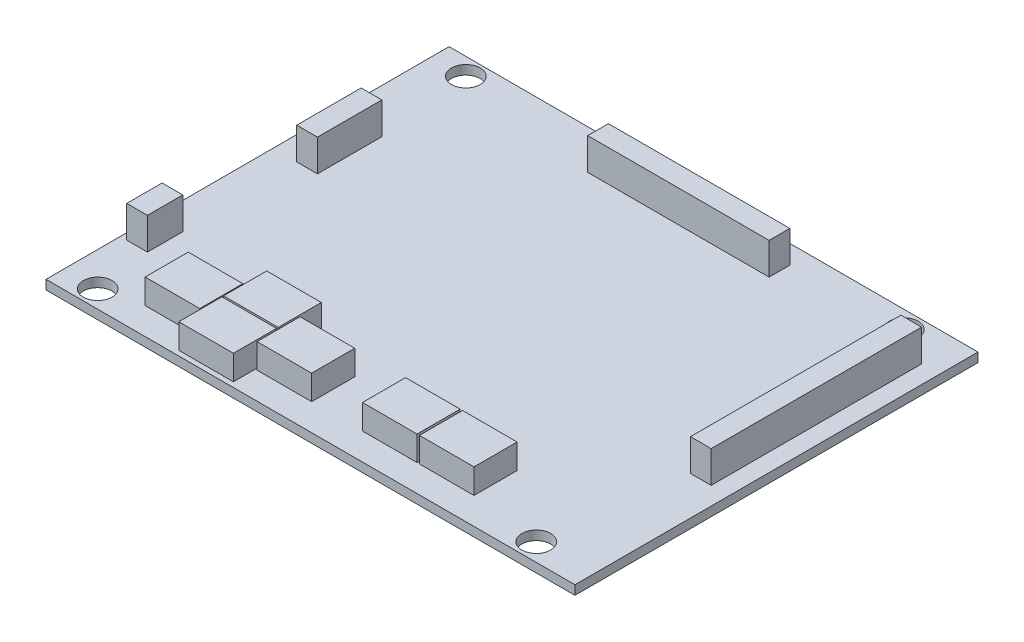
SolidWorks part; units mm, degrees
ref_plane "Front Plane" through (0, 0, 0) normal (0, 0, 1) x (1, 0, 0)
ref_plane "Top Plane" through (0, 0, 0) normal (0, 1, 0) x (1, 0, 0)
ref_plane "Right Plane" through (0, 0, 0) normal (1, 0, 0) x (0, 0, -1)
sketch "Sketch1" plane through (0, 0, 0) normal (0, 1, 0) x (1, 0, 0)
  line L1 (0, 0) -> (92, 0)
  line L2 (0, 0) -> (0, 70.1)
  line L3 (0, 70.1) -> (92, 70.1)
  line L4 (92, 0) -> (92, 70.1)
  circle A0 centre (5.92, 3.07) radius 2.5
  circle A1 centre (82.16, 3.11) radius 2.5
  circle A2 centre (82.16, 67.05) radius 2.5
  circle A3 centre (5.92, 67.1) radius 2.5
  dimension "D3" = 5.92
  dimension "D1" = 92
  dimension "D2" = 70.1
  dimension "D4" = 3.07
  dimension "D5" = 9.84
  dimension "D6" = 3.11
  dimension "D7" = 9.84
  dimension "D8" = 3.05
  dimension "D9" = 3
  dimension "D10" = 5.92
extrude "Y+ PCB extr" add sketch "Sketch1" along normal blind 1.6
sketch "Sketch2" plane through (0, 1.6, 0) normal (0, 1, 0) x (1, 0, 0)
  line L0 (0, 70.1) -> (0, 0) construction
  line L1 (31, 66.82) -> (62.55, 66.82)
  line L2 (31, 66.82) -> (31, 63.22)
  line L3 (31, 63.22) -> (62.55, 63.22)
  line L4 (62.55, 66.82) -> (62.55, 63.22)
  line L5 (4.12, 50.69) -> (7.72, 50.69)
  line L6 (4.12, 50.69) -> (4.12, 39.49)
  line L7 (4.12, 39.49) -> (7.72, 39.49)
  line L8 (7.72, 50.69) -> (7.72, 39.49)
  line L9 (1.12, 19.07) -> (4.72, 19.07)
  line L10 (1.12, 19.07) -> (1.12, 12.92)
  line L11 (1.12, 12.92) -> (4.72, 12.92)
  line L12 (4.72, 19.07) -> (4.72, 12.92)
  line L13 (85.28, 63.41) -> (88.88, 63.41)
  line L14 (85.28, 63.41) -> (85.28, 26.81)
  line L15 (85.28, 26.81) -> (88.88, 26.81)
  line L16 (88.88, 63.41) -> (88.88, 26.81)
  line L17 (92, 70.1) -> (0, 70.1) construction
  line L18 (92, 0) -> (92, 70.1) construction
  line L19 (0, 0) -> (92, 0) construction
  dimension "D1" = 31
  dimension "D2" = 3.28
  dimension "D3" = 3.6
  dimension "D4" = 31.55
  dimension "D5" = 6.69
  dimension "D6" = 3.12
  dimension "D7" = 3.6
  dimension "D8" = 36.6
  dimension "D9" = 19.41
  dimension "D10" = 4.12
  dimension "D11" = 11.2
  dimension "D12" = 3.6
  dimension "D13" = 3.6
  dimension "D14" = 6.15
  dimension "D15" = 1.12
  dimension "D16" = 12.92
extrude "Y+ headers extr" add sketch "Sketch2" along normal blind 5.54
sketch "Sketch3" plane through (0, 1.6, 0) normal (0, 1, 0) x (1, 0, 0)
  line L1 (12.57, 12.17) -> (22.07, 12.17)
  line L2 (12.57, 12.17) -> (12.57, 4.67)
  line L3 (12.57, 4.67) -> (22.07, 4.67)
  line L4 (22.07, 12.17) -> (22.07, 4.67)
  line L24 (0, 70.1) -> (0, 0) construction
  line L25 (0, 0) -> (92, 0) construction
  line L26 (22.23, 8.36) -> (31.73, 8.36)
  line L27 (22.23, 8.36) -> (22.23, 0.86)
  line L28 (22.23, 0.86) -> (31.73, 0.86)
  line L29 (31.73, 8.36) -> (31.73, 0.86)
  line L30 (22.23, 16.16) -> (31.73, 16.16)
  line L31 (22.23, 16.16) -> (22.23, 8.66)
  line L32 (22.23, 8.66) -> (31.73, 8.66)
  line L33 (31.73, 16.16) -> (31.73, 8.66)
  line L34 (32.03, 12.17) -> (41.53, 12.17)
  line L35 (32.03, 12.17) -> (32.03, 4.67)
  line L36 (32.03, 4.67) -> (41.53, 4.67)
  line L37 (41.53, 12.17) -> (41.53, 4.67)
  line L38 (50.37, 12.17) -> (59.87, 12.17)
  line L39 (50.37, 12.17) -> (50.37, 4.67)
  line L40 (50.37, 4.67) -> (59.87, 4.67)
  line L41 (59.87, 12.17) -> (59.87, 4.67)
  line L42 (92, 0) -> (92, 70.1) construction
  line L43 (60.27, 12.17) -> (69.77, 12.17)
  line L44 (60.27, 12.17) -> (60.27, 4.67)
  line L45 (60.27, 4.67) -> (69.77, 4.67)
  line L46 (69.77, 12.17) -> (69.77, 4.67)
  dimension "D1" = 9.5
  dimension "D2" = 7.5
  dimension "D3" = 12.57
  dimension "D4" = 4.67
  dimension "D5" = 9.5
  dimension "D6" = 7.5
  dimension "D7" = 22.23
  dimension "D8" = 0.86
  dimension "D9" = 9.5
  dimension "D10" = 7.5
  dimension "D11" = 22.23
  dimension "D12" = 8.66
  dimension "D13" = 9.5
  dimension "D14" = 7.5
  dimension "D15" = 4.67
  dimension "D16" = 32.03
  dimension "D17" = 9.5
  dimension "D18" = 7.5
  dimension "D19" = 32.13
  dimension "D20" = 4.67
  dimension "D21" = 9.5
  dimension "D22" = 7.5
  dimension "D23" = 4.67
  dimension "D24" = 22.23
extrude "Y+ switches extr" add sketch "Sketch3" along normal blind 4.3
